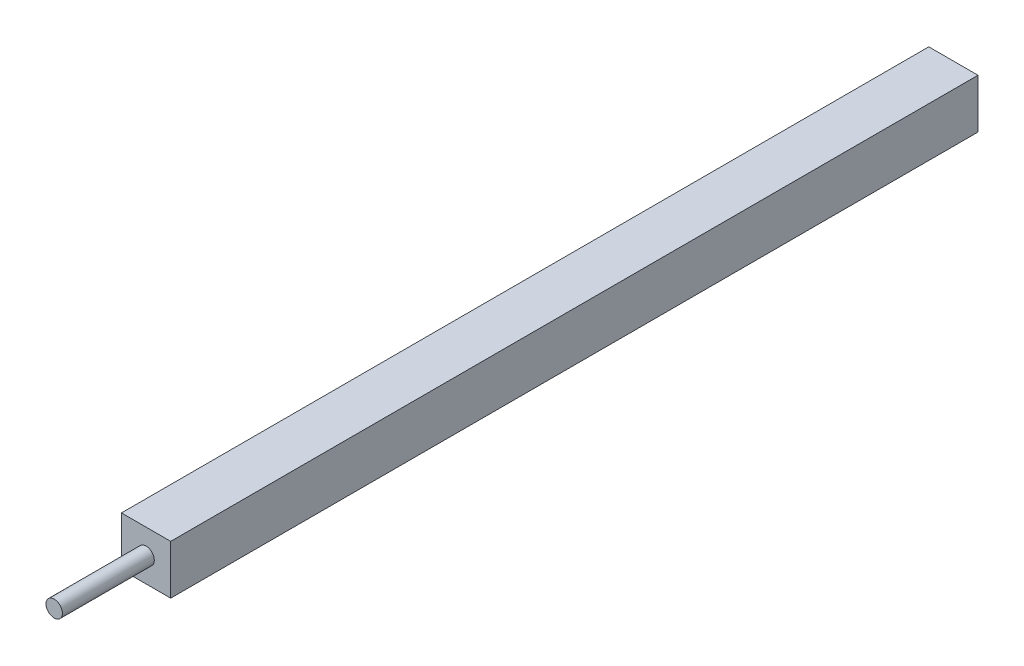
SolidWorks part; units mm, degrees
ref_plane "前视基准面" through (0, 0, 0) normal (0, 0, 1) x (1, 0, 0)
ref_plane "上视基准面" through (0, 0, 0) normal (0, 1, 0) x (1, 0, 0)
ref_plane "右视基准面" through (0, 0, 0) normal (1, 0, 0) x (0, 0, -1)
other "Configuration Table"
sketch "草图1" plane through (0, 0, 0) normal (0, 0, 1) x (1, 0, 0)
  line L1 (0, 0) -> (15, 0)
  line L2 (0, 0) -> (0, -15)
  line L3 (0, -15) -> (15, -15)
  line L4 (15, 0) -> (15, -15)
  dimension "D1" = 15
  dimension "D2" = 15
extrude "凸台-拉伸1" add sketch "草图1" along normal blind 246
sketch "草图2" plane through (0, 0, 246) normal (0, 0, 1) x (1, 0, 0)
  line L0 (0, -7.5) -> (7.5, -7.5) construction
  line L1 (0, 0) -> (0, -15) construction
  line L2 (7.5, -7.5) -> (7.5, 0) construction
  line L3 (15, 0) -> (0, 0) construction
  circle A0 centre (7.5, -7.5) radius 2.5
  dimension "D1" = 5
extrude "凸台-拉伸2" add sketch "草图2" along normal blind 28
